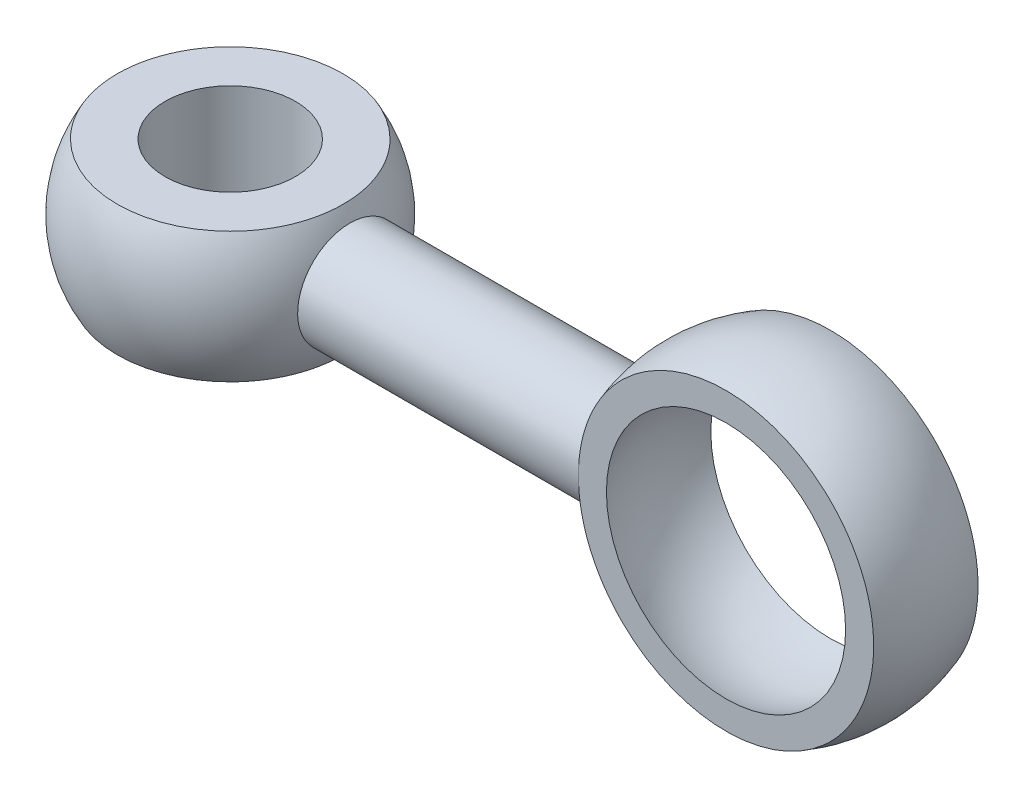
SolidWorks part; units mm, degrees
ref_plane "Ön Düzlem" through (0, 0, 0) normal (0, 0, 1) x (1, 0, 0)
ref_plane "Üst Düzlem" through (0, 0, 0) normal (0, 1, 0) x (1, 0, 0)
ref_plane "Sağ Düzlem" through (0, 0, 0) normal (1, 0, 0) x (0, 0, -1)
sketch "Sketch1" plane through (0, 0, 0) normal (0, 0, 1) x (1, 0, 0)
  line L0 (6.2147, 0) -> (-5.6824, 0) construction
  line L1 (6, 0) -> (-26, 0)
  line L2 (-5.6569, 2) -> (-16.4174, 2)
  arc A0 (-26, 0) -> (-16.4174, 2) centre (-21, 0) cw
  arc A1 (-5.6569, 2) -> (6, 0) centre (0, 0) cw
  point P9 (0, 1.5668)
  point P10 (0, 1.6897)
  point P11 (0, 0)
  point P12 (0, 0)
  point P13 (-1.3721, 0.7988)
  point P14 (-2.0438, 0.7049)
  point P15 (-2.6632, 0.9788)
  dimension "D2" = 5
  dimension "D3" = 6
  dimension "D1" = 21
  dimension "D4" = 2
revolve "Revolve1" add sketch "Sketch1" angle 360 about L0
sketch "Sketch2" plane through (0, 0, 0) normal (0, 0, 1) x (1, 0, 0)
  line L9 (-16.6699, 2.5) -> (-25.3301, 2.5)
  line L11 (-16.6699, -2.5) -> (-25.3301, -2.5)
  line L16 (-5.6569, 2) -> (-16.4174, 2) construction
  arc A2 (-16.4174, 2) -> (-16.4174, -2) centre (-21, 0) ccw construction
  arc A3 (-16.6699, 2.5) -> (-25.3301, 2.5) centre (-21, 0) ccw
  arc A4 (-25.3301, -2.5) -> (-16.6699, -2.5) centre (-21, 0) ccw
  point P7 (0, 0)
  dimension "D2" = 0.5
  dimension "D1" = 5
extrude "Cut-Extrude1" cut sketch "Sketch2" against normal mid plane 10
sketch "Sketch3" plane through (0, 2.5, 0) normal (0, 1, 0) x (1, 0, 0)
  circle A0 centre (-21, 0) radius 2.5
  circle A1 centre (-21, 0) radius 4.3301 construction
  dimension "D1" = 5
extrude "Cut-Extrude2" cut sketch "Sketch3" against normal blind 10
sketch "Sketch4" plane through (0, 0, 0) normal (0, 1, 0) x (1, 0, 0)
  line L1 (-5.6569, 2) -> (5.6569, 2)
  line L3 (-5.6569, -2) -> (5.6569, -2)
  line L5 (-5.6569, 2) -> (-16.4174, 2) construction
  line L6 (-16.4174, -2) -> (-5.6569, -2) construction
  arc A0 (-5.6569, -2) -> (-5.6569, 2) centre (0, 0) ccw construction
  arc A1 (-5.6569, -2) -> (5.6569, -2) centre (0, 0) ccw
  arc A2 (5.6569, 2) -> (-5.6569, 2) centre (0, 0) ccw
extrude "Cut-Extrude4" cut sketch "Sketch4" against normal through all both and the other way through all
sketch "Sketch5" plane through (0, 0, -2) normal (0, 0, -1) x (-1, 0, 0)
  circle A0 centre (0, 0) radius 4.5
  dimension "D1" = 9
extrude "Cut-Extrude5" cut sketch "Sketch5" against normal up to next
sketch "Sketch6" plane through (0, 0, 0) normal (0, 0, 1) x (1, 0, 0)
  line L0 (0, 8.6128) -> (0, -11.2043) construction
  line L1 (0, 5) -> (0, -5)
  arc A0 (0, 5) -> (0, -5) centre (0, 0) ccw
  circle A1 centre (0, 0) radius 5.6569 construction
  dimension "D1" = 5
revolve "Cut-Revolve1" cut sketch "Sketch6" angle 360 about L0
